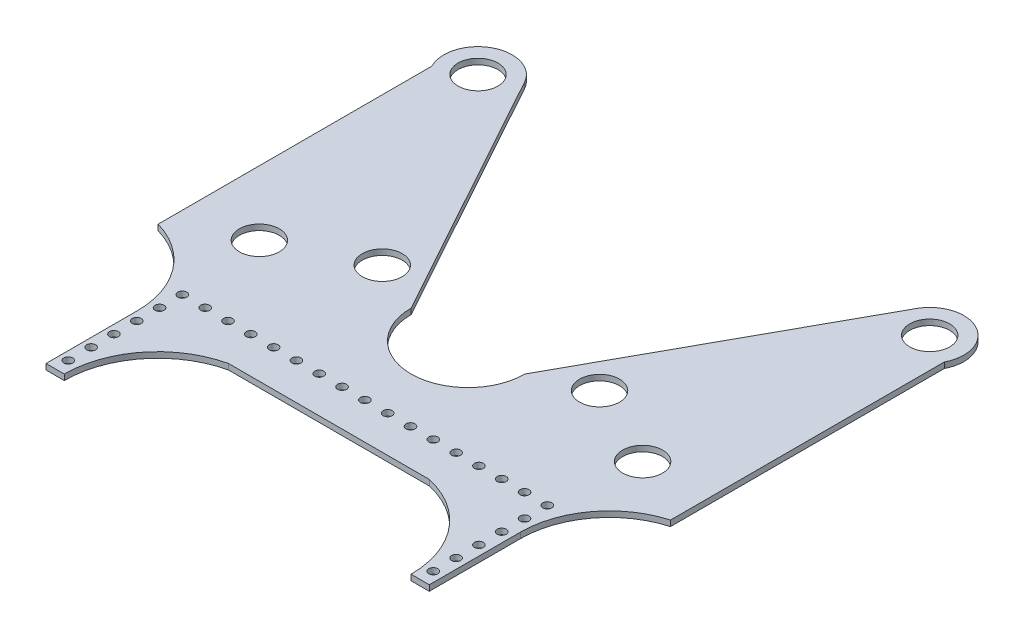
SolidWorks part; units mm, degrees
ref_plane "Front Plane" through (0, 0, 0) normal (0, 0, 1) x (1, 0, 0)
ref_plane "Top Plane" through (0, 0, 0) normal (0, 1, 0) x (1, 0, 0)
ref_plane "Right Plane" through (0, 0, 0) normal (1, 0, 0) x (0, 0, -1)
sketch "Sketch1" plane through (0, 0, 0) normal (0, 1, 0) x (1, 0, 0)
  line L0 (142.6324, 111.9846) -> (142.6324, -40.4154)
  line L1 (31.75, -10.4784) -> (108.9183, 129.7307)
  line L2 (-106.68, -54.9284) -> (106.68, -54.9284) construction
  line L3 (-106.68, -69.6551) -> (-106.68, -42.2284)
  line L4 (0, -42.2284) -> (106.68, -42.2284) construction
  line L5 (106.68, -66.4366) -> (106.68, -42.2284)
  line L6 (-31.75, -10.4784) -> (-108.9183, 129.7307)
  line L7 (31.75, -10.4784) -> (108.9183, 129.7307)
  line L8 (-106.68, -87.976) -> (-106.68, -138.776)
  line L9 (106.68, -87.976) -> (106.68, -138.776)
  line L10 (-106.68, -69.6551) -> (-106.68, -87.976)
  line L11 (-55.88, -87.976) -> (55.88, -87.976)
  line L12 (106.68, -66.4366) -> (106.68, -87.976)
  line L13 (-106.68, -87.976) -> (-96.52, -87.976) construction
  line L14 (-106.68, -87.976) -> (-106.68, -138.776)
  line L15 (-106.68, -138.776) -> (-96.52, -138.776)
  line L16 (-96.52, -87.976) -> (-96.52, -138.776)
  line L17 (106.68, -138.776) -> (96.52, -138.776)
  line L18 (55.88, -87.976) -> (-55.88, -87.976)
  line L19 (96.52, -87.976) -> (96.52, -138.776)
  line L20 (-106.68, -87.976) -> (-96.52, -87.976) construction
  line L21 (-96.52, -87.976) -> (-106.68, -87.976) construction
  line L22 (96.52, -87.976) -> (106.68, -87.976) construction
  line L23 (106.68, -87.976) -> (96.52, -87.976) construction
  line L24 (55.88, -87.976) -> (96.52, -87.976) construction
  line L25 (96.52, -87.976) -> (55.88, -87.976) construction
  line L26 (-96.52, -87.976) -> (-55.88, -87.976) construction
  line L27 (-55.88, -87.976) -> (-96.52, -87.976) construction
  line L28 (-106.68, -42.2284) -> (0, -42.2284) construction
  line L29 (-142.6324, 111.9846) -> (-142.6324, -40.4154)
  arc A0 (-31.75, -10.4784) -> (31.75, -10.4784) centre (0, -10.4784) ccw
  arc A1 (-108.9183, 129.7307) -> (-142.6324, 111.9846) centre (-125.7268, 120.7655) ccw
  circle A2 centre (-60.4845, 2.2216) radius 11.1125
  arc A3 (31.75, -10.4784) -> (0, 21.2716) centre (0, -10.4784) ccw construction
  arc A4 (0, 21.2716) -> (-31.75, -10.4784) centre (0, -10.4784) ccw construction
  arc A5 (-96.52, -138.776) -> (-55.88, -87.976) centre (-44.45, -138.776) cw
  arc A6 (96.52, -138.776) -> (55.88, -87.976) centre (44.45, -138.776) ccw
  circle A7 centre (-125.7268, 120.7655) radius 11.1125
  circle A8 centre (-60.4845, 2.2216) radius 19.05 construction
  circle A9 centre (60.4845, 2.2216) radius 19.05 construction
  arc A10 (108.9183, 129.7307) -> (142.6324, 111.9846) centre (125.7268, 120.7655) cw
  circle A11 centre (125.7268, 120.7655) radius 11.1125
  circle A12 centre (-101.9175, -67.6284) radius 2.4892
  arc A13 (-142.6324, 111.9846) -> (-108.9183, 129.7307) centre (-125.7268, 120.7655) ccw construction
  arc A14 (142.6324, 111.9846) -> (108.9183, 129.7307) centre (125.7268, 120.7655) cw construction
  circle A15 centre (60.4845, 2.2216) radius 11.1125
  circle A16 centre (-89.2175, -67.6284) radius 2.4892
  circle A17 centre (-76.5175, -67.6284) radius 2.4892
  circle A18 centre (-63.8175, -67.6284) radius 2.4892
  circle A19 centre (-51.1175, -67.6284) radius 2.4892
  circle A20 centre (-38.4175, -67.6284) radius 2.4892
  circle A21 centre (-25.7175, -67.6284) radius 2.4892
  circle A22 centre (-13.0175, -67.6284) radius 2.4892
  circle A23 centre (-0.3175, -67.6284) radius 2.4892
  circle A24 centre (12.3825, -67.6284) radius 2.4892
  circle A25 centre (25.0825, -67.6284) radius 2.4892
  circle A26 centre (37.7825, -67.6284) radius 2.4892
  circle A27 centre (50.4825, -67.6284) radius 2.4892
  circle A28 centre (63.1825, -67.6284) radius 2.4892
  circle A29 centre (75.8825, -67.6284) radius 2.4892
  circle A30 centre (88.5825, -67.6284) radius 2.4892
  circle A31 centre (101.2825, -67.6284) radius 2.4892
  circle A32 centre (-101.9175, -80.3284) radius 2.4892
  circle A33 centre (-101.9175, -93.0284) radius 2.4892
  circle A34 centre (-101.9175, -105.7284) radius 2.4892
  circle A35 centre (-101.9175, -118.4284) radius 2.4892
  circle A36 centre (-101.9175, -131.1284) radius 2.4892
  circle A37 centre (101.2825, -80.3284) radius 2.4892
  circle A38 centre (101.2825, -93.0284) radius 2.4892
  circle A39 centre (101.2825, -105.7284) radius 2.4892
  circle A40 centre (101.2825, -118.4284) radius 2.4892
  circle A41 centre (101.2825, -131.1284) radius 2.4892
  arc A42 (-106.68, -87.976) -> (-142.6324, -40.4154) centre (-156.1145, -87.976) ccw
  arc A43 (106.68, -87.976) -> (142.6324, -40.4154) centre (156.1145, -87.976) cw
  circle A46 centre (-106.68, -20.0034) radius 11.1125
  circle A47 centre (106.68, -20.0034) radius 11.1125
  dimension "D3" = 52.07
  dimension "D12" = 31.75
  dimension "D13" = 22.225
  dimension "D14" = 38.1
  dimension "D15" = 22.225
  dimension "D16" = 19.05
  dimension "D17" = 4.9784
  dimension "D18" = 49.4345
  dimension "D1" = 44.45
  dimension "D2" = 45.7476
  dimension "D4" = 88.9
  dimension "D5" = 4.7625
  dimension "D6" = 25.4
  dimension "D7" = 12.7
  dimension "D8" = 12.7
  dimension "D9" = 12.7
  dimension "D10" = 111.76
  dimension "D11" = 106.68
  dimension "D19" = 152.4
  dimension "D20" = 142.6324
  dimension "D21" = 12.7
extrude "Boss-Extrude1" add sketch "Sketch1" along normal blind 3.175
